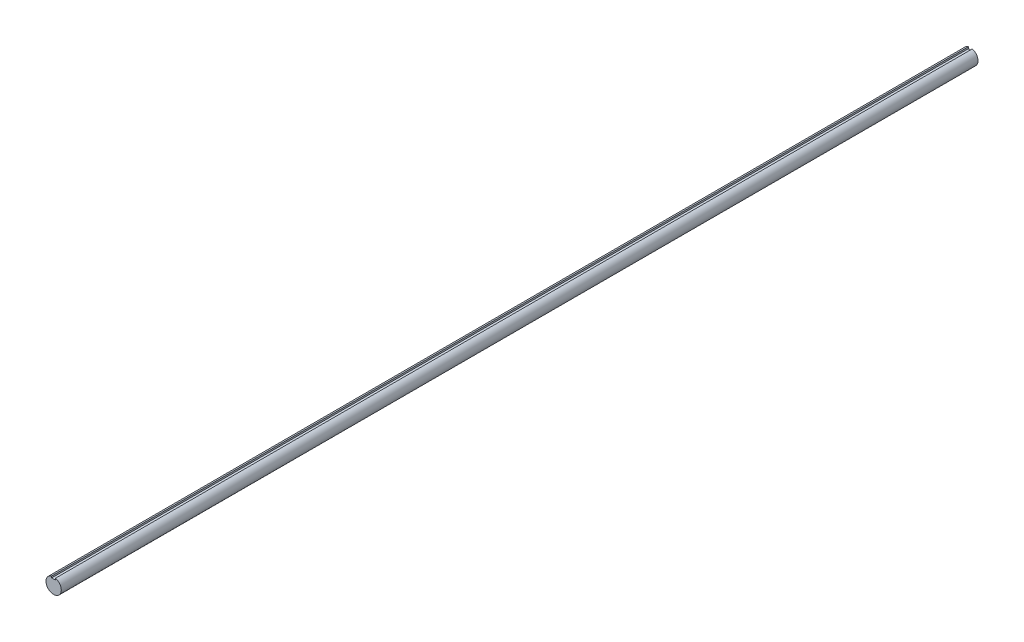
SolidWorks part; units mm, degrees
material "7075-T6 (SN)"
ref_plane "Front Plane" through (0, 0, 0) normal (0, 0, 1) x (1, 0, 0)
ref_plane "Top Plane" through (0, 0, 0) normal (0, 1, 0) x (1, 0, 0)
ref_plane "Right Plane" through (0, 0, 0) normal (1, 0, 0) x (0, 0, -1)
sketch "Sketch1" plane through (0, 0, 0) normal (0, 0, 1) x (1, 0, 0)
  line L0 (-1.5875, 6.1484) -> (-1.5875, 4.7625)
  line L1 (-1.5875, 4.7625) -> (1.5875, 4.7625)
  line L2 (1.5875, 4.7625) -> (1.5875, 6.1484)
  arc A0 (-1.5875, 6.1484) -> (1.5875, 6.1484) centre (0, 0) ccw
  point P6 (0, 6.35)
  dimension "D1" = 12.7
  dimension "D2" = 3.175
  dimension "D3" = 1.5875
extrude "Boss-Extrude1" add sketch "Sketch1" along normal mid plane 762
